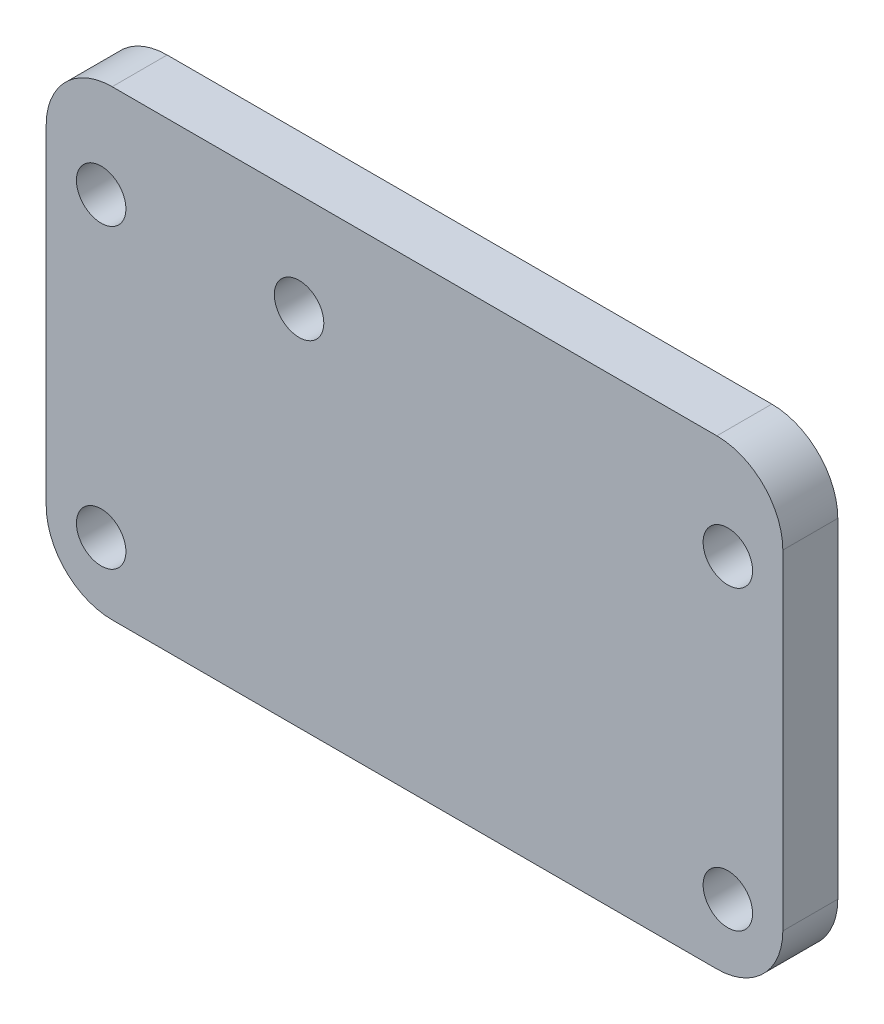
SolidWorks part; units mm, degrees
ref_plane "Спереди" through (0, 0, 0) normal (0, 0, 1) x (1, 0, 0)
ref_plane "Сверху" through (0, 0, 0) normal (0, 1, 0) x (1, 0, 0)
ref_plane "Справа" through (0, 0, 0) normal (1, 0, 0) x (0, 0, -1)
sketch "Эскиз1" plane through (0, 0, 0) normal (0, 0, 1) x (1, 0, 0)
  line L1 (0, 0) -> (67, 0)
  line L2 (0, 0) -> (0, 42)
  line L3 (0, 42) -> (67, 42)
  line L4 (67, 0) -> (67, 42)
  dimension "D1" = 42
  dimension "D2" = 67
extrude "Бобышка-Вытянуть1" add sketch "Эскиз1" along normal blind 5
sketch "Эскиз2" plane through (0, 0, 0) normal (0, 0, -1) x (-1, 0, 0)
  line L0 (-67, 42) -> (0, 42) construction
  line L1 (0, 0) -> (-67, 0) construction
  line L2 (0, 42) -> (0, 0) construction
  line L3 (-67, 0) -> (-67, 42) construction
  circle A0 centre (-62, 6) radius 2.25
  circle A1 centre (-62, 33) radius 2.25
  circle A2 centre (-5, 6) radius 2.25
  circle A3 centre (-5, 33) radius 2.25
  dimension "D1" = 4.5
  dimension "D2" = 9
  dimension "D3" = 6
  dimension "D4" = 5
  dimension "D5" = 5
extrude "Вырез-Вытянуть1" cut sketch "Эскиз2" against normal blind 5
fillet "Скругление1" radius 6 4 edges at (0, 0, 2.5) (0, 42, 2.5) (67, 0, 2.5) (67, 42, 2.5)
sketch "Эскиз4" plane through (0, 0, 5) normal (0, 0, 1) x (1, 0, 0)
  line L0 (5, 33) -> (62, 33) construction
  line L2 (0, 36) -> (0, 6) construction
  circle A0 centre (23, 33) radius 2.25
  point P6 (0, 0)
  dimension "D2" = 4.5
  dimension "D1" = 23
extrude "Вырез-Вытянуть2" cut sketch "Эскиз4" against normal blind 10
sketch "Эскиз3" plane through (0, 0, 0) normal (0, 0, -1) x (-1, 0, 0)
  line L0 (-61, 42) -> (-6, 42) construction
  line L1 (-55, 36) -> (-12, 36)
  line L2 (-55, 36) -> (-55, 30)
  line L3 (-55, 30) -> (-12, 30)
  line L4 (-12, 36) -> (-12, 30)
  line L8 (-30, 36) -> (-16, 36)
  line L9 (-30, 36) -> (-30, 30)
  line L10 (-30, 30) -> (-16, 30)
  line L11 (-16, 36) -> (-16, 30)
  circle A0 centre (-23, 33) radius 2.25 construction
  circle A1 centre (-62, 33) radius 2.25 construction
  circle A2 centre (-5, 33) radius 2.25 construction
  point P6 (-55, 33)
  dimension "D3" = 7
  dimension "D4" = 7
  dimension "D1" = 6
  dimension "D2" = 9
  dimension "D5" = 7
  dimension "D6" = 7
extrude "Бобышка-Вытянуть2" add sketch "Эскиз3" along normal blind 4 contours L1 L11 L3 L4 | L9 L1 L2 L3
